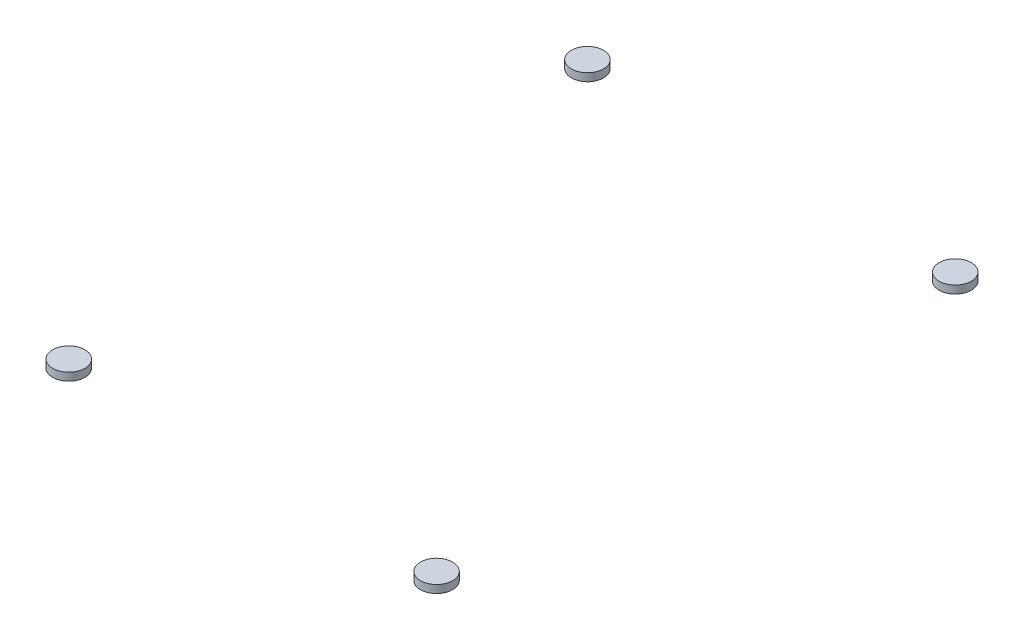
SolidWorks part; units mm, degrees
ref_plane "Front Plane" through (0, 0, 0) normal (0, 0, 1) x (1, 0, 0)
ref_plane "Top Plane" through (0, 0, 0) normal (0, 1, 0) x (1, 0, 0)
ref_plane "Right Plane" through (0, 0, 0) normal (1, 0, 0) x (0, 0, -1)
sketch "Sketch1" plane through (0, 0, 0) normal (0, 1, 0) x (1, 0, 0)
  circle A0 centre (-23.4, 48) radius 2.05
extrude "Boss-Extrude1" add sketch "Sketch1" along normal blind 1 separate body
sketch "Sketch2" plane through (0, 0, 0) normal (0, 1, 0) x (1, 0, 0)
  circle A0 centre (-23.4, -18) radius 2.05
extrude "Boss-Extrude2" add sketch "Sketch2" along normal blind 1 separate body
sketch "Sketch3" plane through (0, 0, 0) normal (0, 1, 0) x (1, 0, 0)
  circle A0 centre (23.4, 48) radius 2.05
extrude "Boss-Extrude3" add sketch "Sketch3" along normal blind 1 separate body
sketch "Sketch4" plane through (0, 0, 0) normal (0, 1, 0) x (1, 0, 0)
  circle A0 centre (23.4, -18) radius 2.05
extrude "Boss-Extrude4" add sketch "Sketch4" along normal blind 1 separate body
